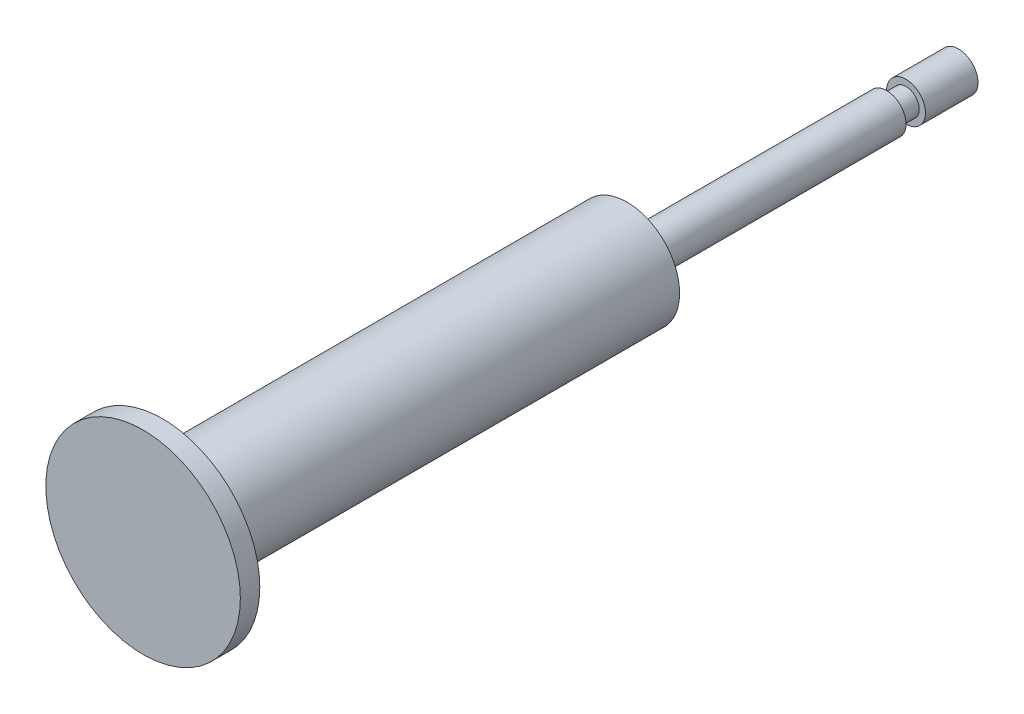
SolidWorks part; units mm, degrees
ref_plane "Plano frontal" through (0, 0, 0) normal (0, 0, 1) x (1, 0, 0)
ref_plane "Plano superior" through (0, 0, 0) normal (0, 1, 0) x (1, 0, 0)
ref_plane "Plano direito" through (0, 0, 0) normal (1, 0, 0) x (0, 0, -1)
sketch "Esboço1" plane through (0, 0, 0) normal (1, 0, 0) x (0, 0, -1)
  line L0 (-72.3911, 0) -> (88.0334, 0) construction
  line L1 (-44.6537, 0) -> (-44.6537, -12.5)
  line L2 (-44.6537, -12.5) -> (-40.6537, -12.5)
  line L3 (-40.6537, -12.5) -> (-40.6537, -6.75)
  line L4 (-40.6537, -6.75) -> (17.5463, -6.75)
  line L5 (17.5463, -6.75) -> (20, -2.5)
  line L6 (0, 0) -> (0, -2.5)
  line L7 (0, -2.5) -> (20, -2.5)
  line L8 (-44.6537, 0) -> (0, 0)
  dimension "D1" = 25
  dimension "D2" = 13.5
  dimension "D3" = 62.2
  dimension "D4" = 5
  dimension "D5" = 120
  dimension "D6" = 20
  dimension "D7" = 4
revolve "Revolução1" add sketch "Esboço1" angle 360 about L0
sketch "Esboço2" plane through (0, 0, 40.6537) normal (0, 0, -1) x (-1, 0, 0)
  circle A0 centre (0, 0) radius 12.5 construction
  circle A1 centre (0, 0) radius 6.75 construction
  circle A2 centre (0, 0) radius 12.5
  circle A3 centre (0, 0) radius 6.75
extrude "Corte-extrusão1" cut sketch "Esboço2" against normal blind 1.5
sketch "Esboço3" plane through (0, 0, 44.6537) normal (0, 0, 1) x (1, 0, 0)
  circle A0 centre (0, 0) radius 2.5 construction
  circle A1 centre (0, 0) radius 2.5
extrude "Ressalto-extrusão1" add sketch "Esboço3" against normal blind 104.8
ref_plane "Plano1" through (0, 0, -53.3963) normal (0, 0, -1) x (-1, 0, 0)
sketch "Esboço4" plane through (0, 0, -53.3963) normal (0, 0, -1) x (-1, 0, 0)
  circle A0 centre (0, 0) radius 2.5 construction
  circle A1 centre (0, 0) radius 2.5
  circle A2 centre (0, 0) radius 1.7
  dimension "D1" = 3.4
extrude "Corte-extrusão2" cut sketch "Esboço4" against normal blind 2.5
